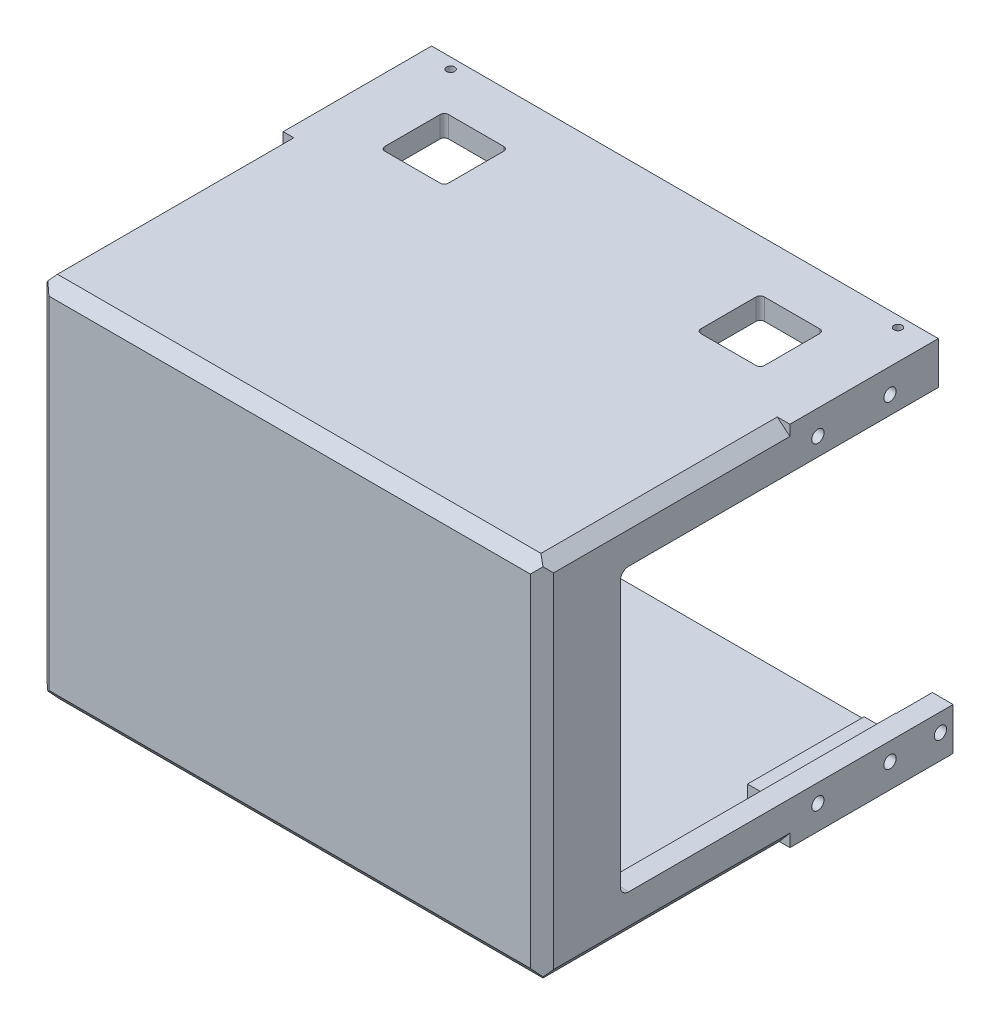
SolidWorks part; units mm, degrees
ref_plane "Front Plane" through (0, 0, 0) normal (0, 0, 1) x (1, 0, 0)
ref_plane "Top Plane" through (0, 0, 0) normal (0, 1, 0) x (1, 0, 0)
ref_plane "Right Plane" through (0, 0, 0) normal (1, 0, 0) x (0, 0, -1)
sketch "Sketch1" plane through (0, 0, 0) normal (0, 0, 1) x (1, 0, 0)
  line L1 (-59.76, -43.25) -> (59.76, -43.25)
  line L2 (-59.76, -43.25) -> (-59.76, 43.25)
  line L3 (-59.76, 43.25) -> (59.76, 43.25)
  line L4 (59.76, -43.25) -> (59.76, 43.25)
  point P4 (0, -43.25)
  point P6 (-59.76, 0)
  dimension "D1" = 86.5
  dimension "D2" = 119.52
extrude "Boss-Extrude1" add sketch "Sketch1" along normal blind 88.24
shell "Shell1" thickness 5
chamfer "Chamfer1" distance 2.5 angle 50 4 edges at (0, -43.25, 88.24) (59.76, 0, 88.24) (0, 43.25, 88.24) (-59.76, 0, 88.24)
chamfer "Chamfer2" distance 2.5 angle 50 1 edges at (-59.76, 43.25, 42.87)
chamfer "Chamfer3" distance 2.5 angle 50 3 edges at (-59.76, -43.25, 42.87) (59.76, -43.25, 42.87) (59.76, 43.25, 42.87)
sketch "Sketch3" plane through (59.76, 0, 0) normal (1, 0, 0) x (0, 0, -1)
  line L0 (0, 43.25) -> (0, 33.25)
  line L1 (0, -40.2706) -> (0, 40.75) construction
  line L2 (0, -43.25) -> (0, -33.25)
  line L4 (0, 33.25) -> (-70, 33.25)
  line L5 (0, 33.25) -> (0, -33.25)
  line L6 (0, -33.25) -> (-70, -33.25)
  line L7 (-70, 33.25) -> (-70, -33.25)
  line M6 (0, -40.2706) -> (0, 40.75)
  dimension "D1" = 10
  dimension "D2" = 10
  dimension "D3" = 70
extrude "Cut-Extrude1" cut sketch "Sketch3" against normal up to next contours L4 L7 L6 M6
fillet "Fillet1" radius 2 2 edges at (57.26, -33.25, 70) (57.26, 33.25, 70)
mirror "Mirror1" about plane through (0, 0, 0) normal (1, 0, 0) of "Cut-Extrude1", "Fillet1"
sketch "Sketch4" plane through (0, 0, 0) normal (0, 0, -1) x (-1, 0, 0)
  line L0 (-56.7806, 43.25) -> (57.26, 43.25) construction
  line L1 (-54.76, 38.25) -> (54.76, 38.25)
  line L2 (-54.76, 38.25) -> (-54.76, 43.25)
  line L3 (-54.76, 43.25) -> (54.76, 43.25)
  line L4 (54.76, 38.25) -> (54.76, 43.25)
  line L5 (54.76, 38.25) -> (54.76, -38.25) construction
  dimension "D1" = 0
extrude "Boss-Extrude2" add sketch "Sketch4" along normal blind 5
sketch "Sketch5" plane through (0, 43.25, 0) normal (0, 1, 0) x (1, 0, 0)
  line L0 (-54.76, 0) -> (54.76, 0) construction
  line L1 (-54.76, 5) -> (-54.76, 0) construction
  line L2 (54.76, 5) -> (54.76, 0) construction
  circle A0 centre (-52.76, 2.5) radius 0.95
  circle A1 centre (52.76, 2.5) radius 0.95
  point P10 (0, 0)
  point P11 (-54.76, 2.5)
  point P12 (0, 0)
  point P13 (0, 0)
  point P14 (0, 0)
  point P15 (0, 0)
  dimension "D3" = 1.9
  dimension "D4" = 1.9
  dimension "D1" = 2
  dimension "D2" = 2
extrude "Cut-Extrude2" cut sketch "Sketch5" against normal up to next
sketch "Sketch6" plane through (0, 0, 0) normal (0, 0, -1) x (-1, 0, 0)
  line L0 (-59.76, -33.25) -> (-54.86, -33.25)
  line L1 (-54.76, -33.25) -> (-59.76, -33.25) construction
  line L2 (-59.76, -33.25) -> (-59.76, -40.2706)
  line L3 (-59.76, -40.2706) -> (-57.26, -43.25)
  line L4 (-54.86, -33.25) -> (-54.86, -43.25)
  line L5 (56.7806, -43.25) -> (-57.26, -43.25) construction
  line L6 (-54.86, -43.25) -> (-57.26, -43.25)
  dimension "D1" = 4.9
extrude "Boss-Extrude3" add sketch "Sketch6" along normal blind 8.5
sketch "Sketch8" plane through (0, 0, 0) normal (0, 0, -1) x (-1, 0, 0)
  line L0 (57.26, 43.25) -> (54.76, 43.25) construction
  line L1 (54.76, 43.25) -> (54.76, 38.25) construction
  line L2 (54.76, 38.25) -> (54.76, 33.25) construction
  line L3 (54.76, 33.25) -> (59.76, 33.25) construction
  line L4 (59.76, 33.25) -> (59.76, 40.2706) construction
  line L5 (59.76, 40.2706) -> (57.26, 43.25) construction
  line L6 (-54.76, 33.25) -> (-54.76, 38.25) construction
  line L7 (-54.76, 38.25) -> (-54.76, 43.25) construction
  line L8 (-54.76, 43.25) -> (-56.7806, 43.25) construction
  line L9 (-56.7806, 43.25) -> (-59.76, 40.75) construction
  line L10 (-59.76, 40.75) -> (-59.76, 33.25) construction
  line L11 (-59.76, 33.25) -> (-54.76, 33.25) construction
  line L12 (57.26, 43.25) -> (54.76, 43.25)
  line L13 (54.76, 43.25) -> (54.76, 38.25)
  line L14 (54.76, 38.25) -> (54.76, 33.25)
  line L15 (54.76, 33.25) -> (59.76, 33.25)
  line L16 (59.76, 33.25) -> (59.76, 40.2706)
  line L17 (59.76, 40.2706) -> (57.26, 43.25)
  line L18 (-54.76, 33.25) -> (-54.76, 38.25)
  line L19 (-54.76, 38.25) -> (-54.76, 43.25)
  line L20 (-54.76, 43.25) -> (-56.7806, 43.25)
  line L21 (-56.7806, 43.25) -> (-59.76, 40.75)
  line L22 (-59.76, 40.75) -> (-59.76, 33.25)
  line L23 (-59.76, 33.25) -> (-54.76, 33.25)
extrude "Boss-Extrude4" add sketch "Sketch8" along normal blind 5
sketch "Sketch10" plane through (0, 0, -5) normal (0, 0, -1) x (-1, 0, 0)
  line L0 (-59.76, 40.75) -> (-59.76, 43.25)
  line L1 (-56.7806, 43.25) -> (-59.76, 43.25)
  line L2 (-59.76, 40.75) -> (-56.7806, 43.25)
extrude "Boss-Extrude6" add sketch "Sketch10" against normal blind 35
sketch "Sketch11" plane through (0, 0, 0) normal (0, 0, -1) x (-1, 0, 0)
  line L0 (59.76, -33.25) -> (54.86, -33.25)
  line L1 (59.76, -33.25) -> (54.76, -33.25) construction
  line L2 (54.86, -33.25) -> (54.86, -43.25)
  line L3 (56.7806, -43.25) -> (-54.86, -43.25) construction
  line L4 (54.86, -43.25) -> (56.7806, -43.25)
  line L5 (56.7806, -43.25) -> (59.76, -40.75)
  line L6 (59.76, -40.75) -> (59.76, -33.25)
  dimension "D1" = 4.9
extrude "Boss-Extrude7" add sketch "Sketch11" along normal blind 8.5
sketch "Sketch13" plane through (0, 0, -5) normal (0, 0, -1) x (-1, 0, 0)
  line L0 (57.26, 43.25) -> (59.76, 43.25)
  line L1 (59.76, 40.2706) -> (59.76, 43.25)
  line L2 (57.26, 43.25) -> (59.76, 40.2706)
extrude "Boss-Extrude8" add sketch "Sketch13" against normal blind 35
sketch "Sketch14" plane through (0, 0, -8.5) normal (0, 0, -1) x (-1, 0, 0)
  line L0 (-59.76, -40.2706) -> (-59.76, -43.25)
  line L1 (-57.26, -43.25) -> (-59.76, -43.25)
  line L2 (59.76, -40.75) -> (59.76, -43.25)
  line L3 (56.7806, -43.25) -> (59.76, -43.25)
  line L4 (56.7806, -43.25) -> (59.76, -40.75)
  line L5 (-59.76, -40.2706) -> (-57.26, -43.25)
extrude "Boss-Extrude9" add sketch "Sketch14" against normal blind 38.5
sketch "Sketch15" plane through (59.76, 0, 0) normal (1, 0, 0) x (0, 0, -1)
  line L0 (5, 37.5) -> (-6.4, 37.5) construction
  line L1 (5, 43.25) -> (5, 33.25) construction
  line L2 (-30, 43.25) -> (5, 43.25) construction
  line L3 (-6.4, 37.5) -> (-23.4, 37.5) construction
  line L4 (-6.4, 36.05) -> (-6.4, 33.25) construction
  line L5 (5, 33.25) -> (-68, 33.25) construction
  circle A0 centre (-6.4, 37.5) radius 1.45
  circle A1 centre (-23.4, 37.5) radius 1.45
  dimension "D4" = 2.9
  dimension "D5" = 2.9
  dimension "D1" = 5.75
  dimension "D2" = 11.4
  dimension "D3" = 17
sketch "Sketch16" plane through (0, 38.25, 0) normal (0, -1, 0) x (1, 0, 0)
  line L0 (54.76, 2.5) -> (49.76, 2.5)
  line L1 (54.76, -5) -> (54.76, 68) construction
  line L2 (49.76, 2.5) -> (49.76, 30)
  line L3 (49.76, 30) -> (54.76, 30)
  line L4 (54.76, 83.24) -> (54.76, -5) construction
  line L5 (54.76, -5) -> (-54.76, -5) construction
  line L6 (54.76, 30) -> (54.76, 2.5)
  dimension "D1" = 35
  dimension "D2" = 7.5
  dimension "D3" = 5
extrude "Boss-Extrude10" add sketch "Sketch16" along normal blind 3
mirror "Mirror6" about plane through (0, 0, 0) normal (1, 0, 0) of "Boss-Extrude10"
mirror "Mirror7" about plane through (0, 0, 0) normal (0, 1, 0) of "Mirror6", "Boss-Extrude10"
extrude "Cut-Extrude5" cut sketch "Sketch15" against normal blind 8
mirror "Mirror8" about plane through (0, 0, 0) normal (0, 1, 0) of "Cut-Extrude5" second plane through (0, 0, 0) second plane normal (1, 0, 0)
sketch "Sketch17" plane through (59.76, 0, 0) normal (1, 0, 0) x (0, 0, -1)
  line L0 (-6.4, -37.5) -> (8.5, -37.5) construction
  line L1 (8.5, -33.25) -> (8.5, -43.25) construction
  line L2 (5.5, -37.5) -> (5.5, -43.25) construction
  line L3 (-30, -43.25) -> (8.5, -43.25) construction
  circle A0 centre (5.5, -37.5) radius 1.45
  dimension "D1" = 2.9
extrude "Cut-Extrude6" cut sketch "Sketch17" against normal blind 8
sketch "Sketch18" plane through (-54.86, 0, 0) normal (1, 0, 0) x (0, 0, -1)
  circle A0 centre (5.5, -37.5) radius 1.45 construction
  circle A1 centre (5.5, -37.5) radius 1.45
extrude "Cut-Extrude7" cut sketch "Sketch18" against normal blind 8
sketch "Sketch19" plane through (0, 43.25, 0) normal (0, 1, 0) x (1, 0, 0)
  line L0 (-59.76, -30) -> (-59.76, 5) construction
  line L1 (-44.76, -22) -> (-29.76, -22)
  line L2 (-44.76, -22) -> (-44.76, -7)
  line L3 (-44.76, -7) -> (-29.76, -7)
  line L4 (-29.76, -22) -> (-29.76, -7)
  line L5 (-59.76, 5) -> (59.76, 5) construction
  dimension "D1" = 15
  dimension "D2" = 15
  dimension "D3" = 15
  dimension "D4" = 12
extrude "Cut-Extrude8" cut sketch "Sketch19" against normal blind 5
fillet "Fillet2" radius 1 4 edges at (-29.76, 40.75, 7) (-44.76, 40.75, 7) (-29.76, 40.75, 22) (-44.76, 40.75, 22)
mirror "Mirror10" about plane through (0, 0, 0) normal (1, 0, 0) of "Cut-Extrude8", "Fillet2"
